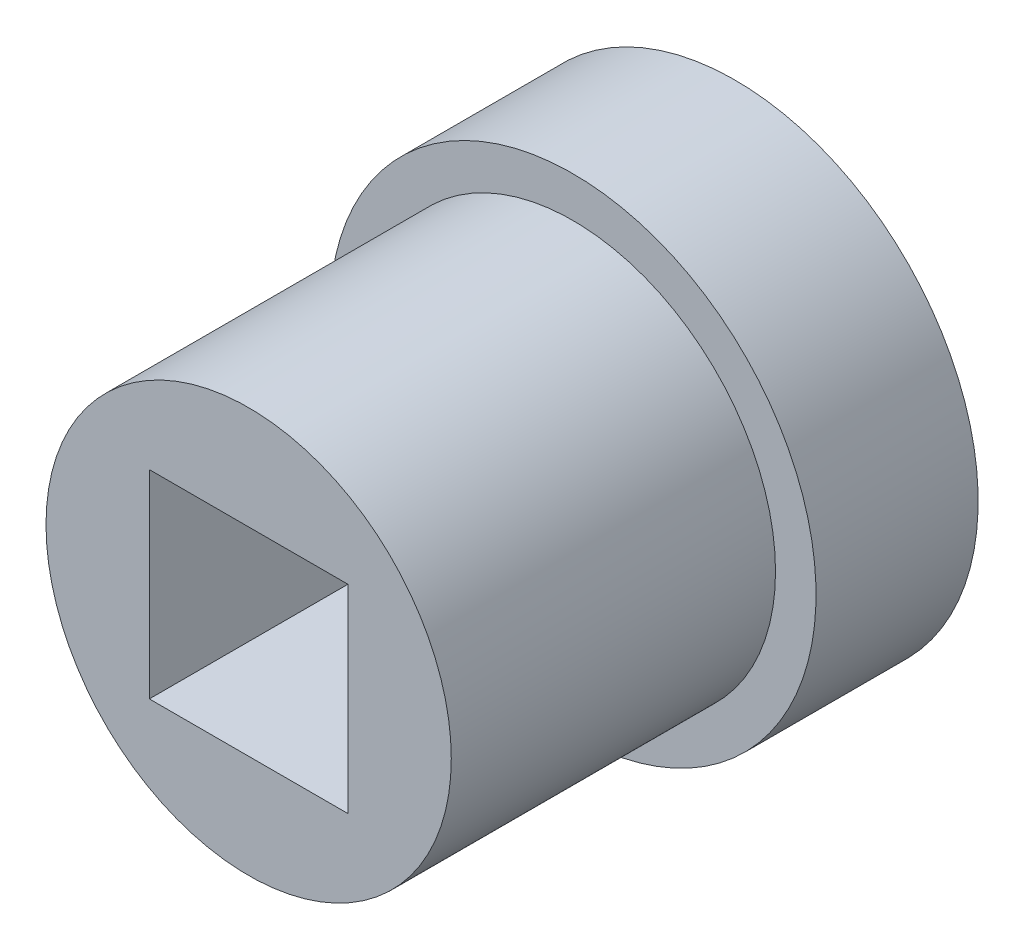
SolidWorks part; units mm, degrees
ref_plane "Front Plane" through (0, 0, 0) normal (0, 0, 1) x (1, 0, 0)
ref_plane "Top Plane" through (0, 0, 0) normal (0, 1, 0) x (1, 0, 0)
ref_plane "Right Plane" through (0, 0, 0) normal (1, 0, 0) x (0, 0, -1)
sketch "Sketch1" plane through (0, 0, 0) normal (0, 0, 1) x (1, 0, 0)
  circle A0 centre (0, 0) radius 12.5
  dimension "D2" = 25
extrude "Boss-Extrude1" add sketch "Sketch1" along normal mid plane 20
sketch "Sketch10" plane through (0, 0, 10) normal (0, 0, 1) x (1, 0, 0)
  circle A0 centre (0, 0) radius 12.5
  dimension "D1" = 25
sketch "Sketch11" plane through (0, 0, -10) normal (0, 0, -1) x (-1, 0, 0)
  circle A0 centre (0, 0) radius 15
  dimension "D1" = 30
extrude "Boss-Extrude2" add sketch "Sketch11" along normal blind 10
sketch "Sketch8" plane through (0, 0, 10) normal (0, 0, 1) x (1, 0, 0)
  line L2 (-6.125, 6.125) -> (6.125, 6.125)
  line L3 (-6.125, 6.125) -> (-6.125, -6.125)
  line L4 (-6.125, -6.125) -> (6.125, -6.125)
  line L5 (6.125, 6.125) -> (6.125, -6.125)
  line L6 (-6.125, 6.125) -> (6.125, -6.125) construction
  line L7 (-6.125, -6.125) -> (6.125, 6.125) construction
  point P5 (0, 0)
  point P14 (0, 0)
  dimension "D1" = 12.25
extrude "Cut-Extrude1" cut sketch "Sketch8" against normal through all
sketch "Sketch12" plane through (0, 0, -20) normal (0, 0, -1) x (-1, 0, 0)
  circle A0 centre (0, 12) radius 1
extrude "Cut-Extrude2" cut sketch "Sketch12" against normal blind 5
pattern_circular "CirPattern1" count 7 over 360 about axis through (0, 0, 0) along (0, 0, 1) of "Cut-Extrude2"
equation "\"drumDiameter\"= 25"
equation "\"D2@Sketch1\"= \"drumDiameter\""
equation "\"drumLength\"=20"
equation "\"foamThickness\"= 5"
equation "\"drumAbove\"= 0.6"
equation "\"holderThicc\"= 2"
equation "\"D1@Boss-Extrude1\"=\"drumLength\""
equation "\"squareBarLength\"= 12.25"
equation "\"D1@Sketch8\"=\"squareBarLength\""
equation "\"D1@Sketch10\"=\"drumDiameter\""
equation "\"toothlen\"= 2.5"
